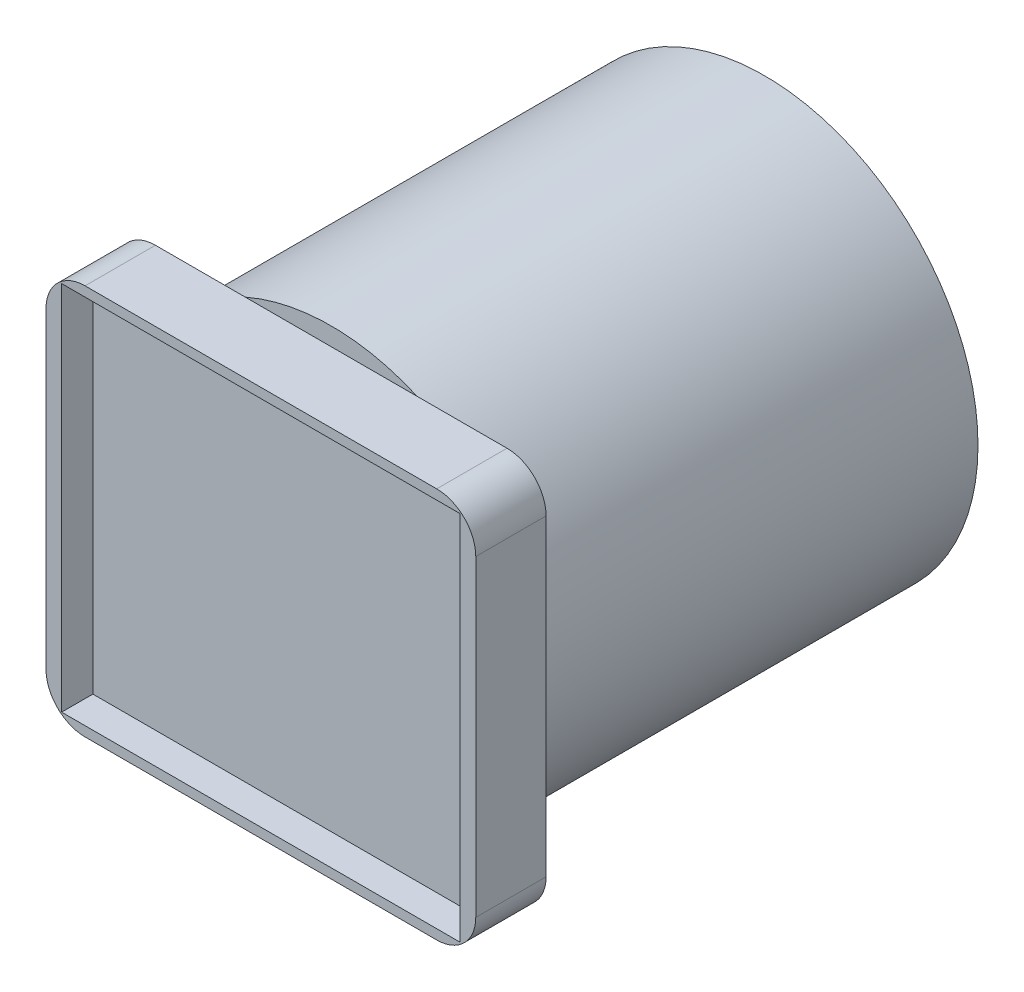
SolidWorks part; units mm, degrees
material "201.0-T43 Insulated Mold Casting (SS)"
ref_plane "Front Plane" through (0, 0, 0) normal (0, 0, 1) x (1, 0, 0)
ref_plane "Top Plane" through (0, 0, 0) normal (0, 1, 0) x (1, 0, 0)
ref_plane "Right Plane" through (0, 0, 0) normal (1, 0, 0) x (0, 0, -1)
sketch "Sketch2" plane through (0, 0, 0) normal (0, 0, 1) x (1, 0, 0)
  line L1 (13.97, -12.7) -> (-13.97, -12.7)
  line L2 (13.97, -12.7) -> (13.97, 12.7)
  line L3 (13.97, 12.7) -> (-13.97, 12.7)
  line L4 (-13.97, -12.7) -> (-13.97, 12.7)
  line L5 (13.97, -12.7) -> (-13.97, 12.7) construction
  line L6 (13.97, 12.7) -> (-13.97, -12.7) construction
  line L11 (12.954, -12.065) -> (-12.954, -12.065)
  line L12 (12.954, -12.065) -> (12.954, 12.065)
  line L13 (12.954, 12.065) -> (-12.954, 12.065)
  line L14 (-12.954, -12.065) -> (-12.954, 12.065)
  line L15 (12.954, -12.065) -> (-12.954, 12.065) construction
  line L16 (12.954, 12.065) -> (-12.954, -12.065) construction
  point P0 (0, 0)
  point P5 (0, 0)
  dimension "D1" = 27.94
  dimension "D2" = 25.4
  dimension "D3" = 25.908
  dimension "D4" = 24.13
extrude "Boss-Extrude1" add sketch "Sketch2" along normal blind 2.032
sketch "Sketch3" plane through (0, 0, 0) normal (0, 0, -1) x (-1, 0, 0)
  line L4 (13.97, -12.7) -> (13.97, 12.7)
  line L5 (13.97, 12.7) -> (-13.97, 12.7)
  line L6 (-13.97, 12.7) -> (-13.97, -12.7)
  line L7 (-13.97, -12.7) -> (13.97, -12.7)
  line L8 (13.97, -12.7) -> (13.97, 12.7)
  line L9 (13.97, 12.7) -> (-13.97, 12.7)
  line L10 (-13.97, 12.7) -> (-13.97, -12.7)
  line L11 (-13.97, -12.7) -> (13.97, -12.7)
  dimension "D1" = 0
extrude "Boss-Extrude2" add sketch "Sketch3" along normal blind 2.54
sketch "Sketch4" plane through (0, 0, -2.54) normal (0, 0, -1) x (-1, 0, 0)
  circle A0 centre (0, 0) radius 13.8748
  dimension "D1" = 27.7495
extrude "Boss-Extrude3" add sketch "Sketch4" along normal blind 28.175 contours A0
fillet "Fillet1" radius 2.54 4 edges at (13.97, -12.7, -0.254) (-13.97, -12.7, -0.254) (-13.97, 12.7, -0.254) (13.97, 12.7, -0.254)
